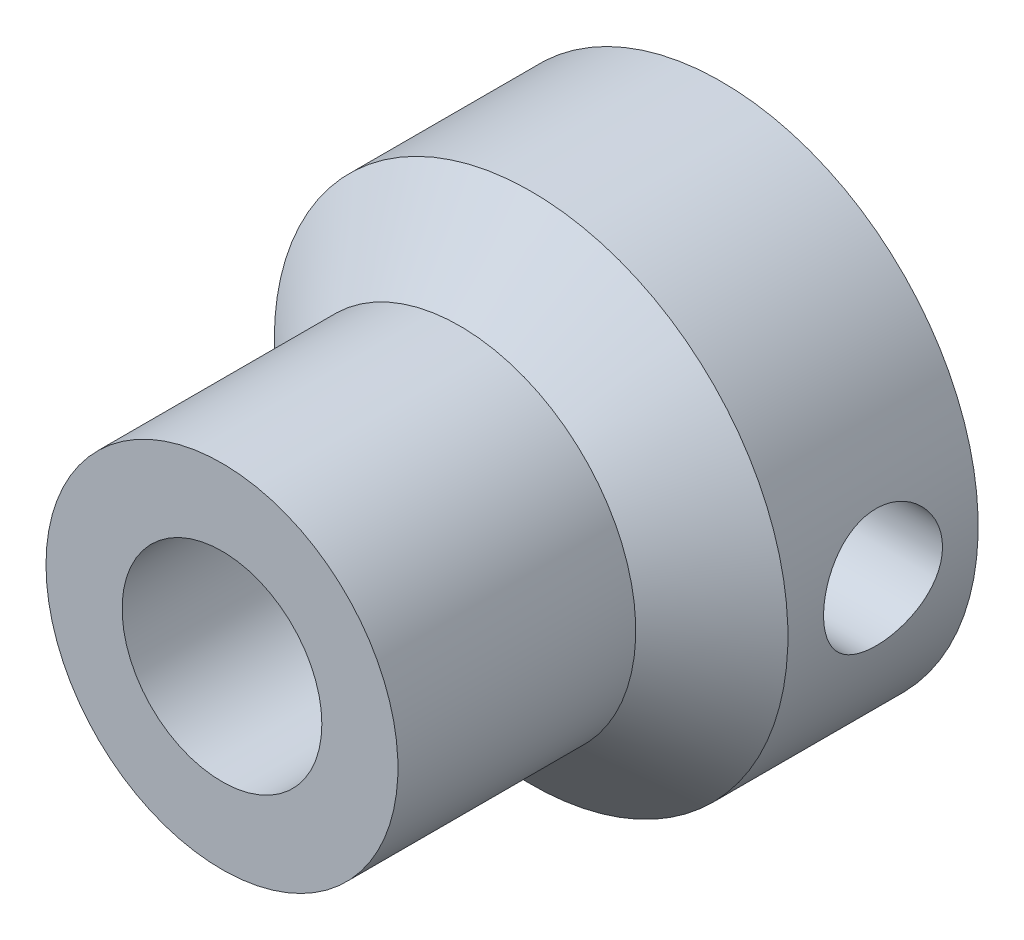
SolidWorks part; units mm, degrees
ref_plane "Top" through (0, 0, 0) normal (0, 0, 1) x (1, 0, 0)
ref_plane "Front" through (0, 0, 0) normal (0, 1, 0) x (1, 0, 0)
ref_plane "Right" through (0, 0, 0) normal (1, 0, 0) x (0, 0, -1)
ref_plane "Base Tangent Plane" through (5.4, 0, 0) normal (1, 0, 0) x (0, 0, -1)
sketch "Body Sketch" plane through (0, 0, 0) normal (0, 1, 0) x (-1, 0, 0)
  line L1 (1, 10.5) -> (3.7, 10.5)
  line L2 (3.7, 10.5) -> (3.7, 5.5)
  line L3 (3.7, 5.5) -> (5.4, 4)
  line L4 (5.4, 4) -> (5.4, 0)
  line L5 (5.4, 0) -> (2.5, 0)
  line L8 (0, 0) -> (0, 10.5) construction
  line L9 (1, 10.5) -> (1, 5)
  line L10 (1, 5) -> (2.5, 5)
  line L11 (2.5, 5) -> (2.5, 0)
  point P5 (2.3608, 0)
  point P8 (0, 0)
  point P12 (0, 0)
  point P13 (2.4003, 0)
  point P14 (0, 0)
  point P15 (0, 0)
  point P16 (0, 0)
  point P17 (1.1596, 10.5)
  point P19 (2.6259, 0)
  point P20 (0.7085, 10.4301)
  dimension "D1" = 4
  dimension "D6" = 5
  dimension "D2" = 10.5
  dimension "D4" = 5.4
  dimension "D3" = 3.7
  dimension "D5" = 2.5
  dimension "D7" = 1
  dimension "D8" = 5
revolve "Body Revolve" add sketch "Body Sketch" angle 360 about L8
hole_wizard "Connector M5x0.8 Tapped Hole" positions "Connector Position Sketch" profile "Sketch5" tap size "M5x0.8" standard "ANSI Metric" end condition through all
sketch "Connector Position Sketch" plane through (0, 0, 10.5) normal (0, 0, 1) x (1, 0, 0)
  point P0 (0, 0)
cosmetic thread "Connector Hole Thread"
sketch "Sketch5" plane through (0, 0, 10.5) normal (1, 0, 0) x (0, -1, 0)
  line L0 (0, 0) -> (0, 10.5)
  line L1 (0, 10.5) -> (2.1, 10.5)
  line L2 (2.1, 10.5) -> (2.1, 0)
  line L5 (2.1, 0) -> (0, 0)
  line L11 (0, -6.35) -> (0, 107.95) construction
  dimension "Thru Tap Drill Dia." = 4.2
  dimension "Thru Tap Drill Depth" = 10.5
hole_wizard "Set Screw 1 M3x0.5 Tapped Hole" positions "Set Screw Position Sketch" profile "Set Screw Profile Sketch" tap size "M3x0.5" standard "ANSI Metric"
sketch3d "Set Screw Position Sketch"
  point P0 (5.4, 0, 2)
  point P3 (0, 0, 0)
  point P5 (0, 0, 0)
  point P6 (0, 0, 0)
  point P7 (0, 0, 0)
  point P8 (5.4, 0, 3.9623)
  dimension "D1" = 2
sketch "Set Screw Profile Sketch" plane through (5.4, 0, 2) normal (0, 1, 0) x (0, 0, -1)
  line L0 (0, 0) -> (0, 2.9)
  line L1 (0, 2.9) -> (1.25, 2.9)
  line L2 (1.25, 2.9) -> (1.25, 0)
  line L5 (1.25, 0) -> (0, 0)
  line L11 (0, -6.35) -> (0, 107.95) construction
  dimension "Thru Tap Drill Dia." = 2.5
  dimension "Thru Tap Drill Depth" = 2.9
cosmetic thread "Set Screw 1 Hole Thread"
pattern_circular "Set Screw 2 Pattern" count 2 over 360 about axis through (0, 0, 2) along (1, 0, 0) of "Set Screw 1 M3x0.5 Tapped Hole"
cosmetic thread "Hole Thread3"
equation "\"Base Diameter\"= 10.8"
equation "\"D4@Body Sketch\"=\"Base Diameter\"/2"
equation "\"D1@Base Tangent Plane\"=\"Base Diameter\"/2"
